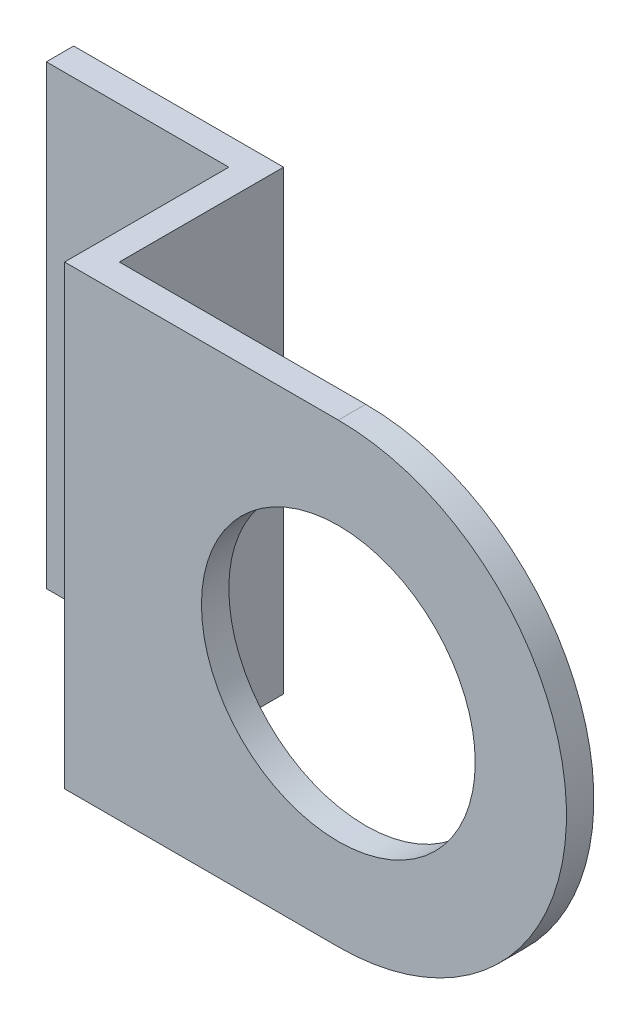
SolidWorks part; units mm, degrees
ref_plane "前视基准面" through (0, 0, 0) normal (0, 0, 1) x (1, 0, 0)
ref_plane "上视基准面" through (0, 0, 0) normal (0, 1, 0) x (1, 0, 0)
ref_plane "右视基准面" through (0, 0, 0) normal (1, 0, 0) x (0, 0, -1)
sketch "草图1" plane through (0, 0, 0) normal (0, 0, 1) x (1, 0, 0)
  line L0 (0, 0) -> (88.5417, 0) construction
  line L1 (60, 50) -> (0, 50)
  line L2 (0, 50) -> (0, -50)
  line L3 (0, -50) -> (60, -50)
  arc A0 (60, -50) -> (60, 50) centre (60, 0) ccw
  circle A1 centre (60, 0) radius 30
  dimension "D2" = 100
  dimension "D3" = 60
  dimension "D1" = 60
extrude "凸台-拉伸1" add sketch "草图1" along normal blind 6
sketch "草图2" plane through (0, 0, 0) normal (0, 1, 0) x (1, 0, 0)
  line L0 (0, 0) -> (0, 30)
  line L1 (0, 30) -> (-40, 30)
  line L2 (-40, 30) -> (-40, 36)
  line L3 (-40, 36) -> (6, 36)
  line L4 (6, 36) -> (6, 0)
  line L5 (60, 0) -> (0, 0) construction
  line L6 (6, 0) -> (0, 0)
  dimension "D1" = 6
  dimension "D2" = 6
  dimension "D3" = 40
  dimension "D4" = 30
extrude "凸台-拉伸2" add sketch "草图2" along normal mid plane 100
